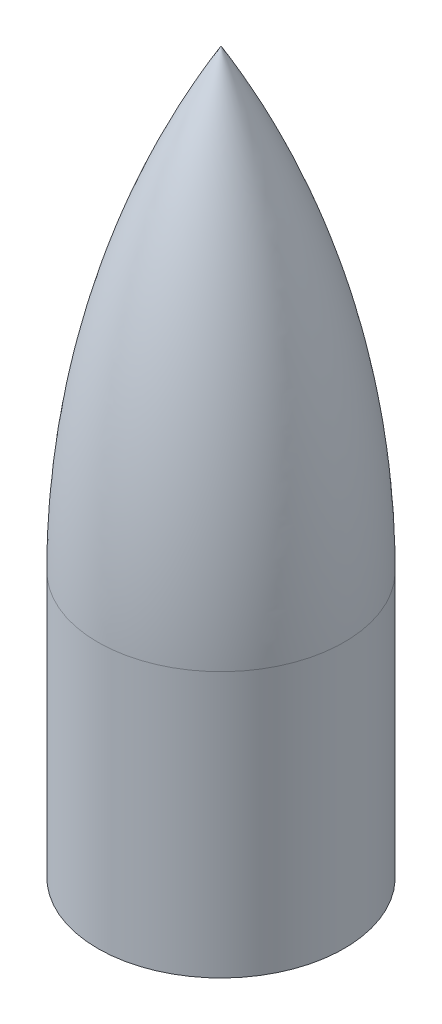
SolidWorks part; units mm, degrees
ref_plane "Plan de face" through (0, 0, 0) normal (0, 0, 1) x (1, 0, 0)
ref_plane "Plan de dessus" through (0, 0, 0) normal (0, 1, 0) x (1, 0, 0)
ref_plane "Plan de droite" through (0, 0, 0) normal (1, 0, 0) x (0, 0, -1)
sketch "Esquisse1" plane through (0, 0, 0) normal (0, 0, 1) x (1, 0, 0)
  line L0 (0, 0) -> (-3.25, 0)
  line L1 (-3.25, 0) -> (-3.25, 7)
  line L2 (0, 0) -> (0, 17.9274) construction
  line L3 (0, 19) -> (0, 0)
  arc A0 (-3.25, 7) -> (0, 19) centre (20.5288, 7) cw
  dimension "D1" = 12
  dimension "D2" = 7
  dimension "D3" = 3.25
revolve "Révolution1" add sketch "Esquisse1" angle 360 about L2
